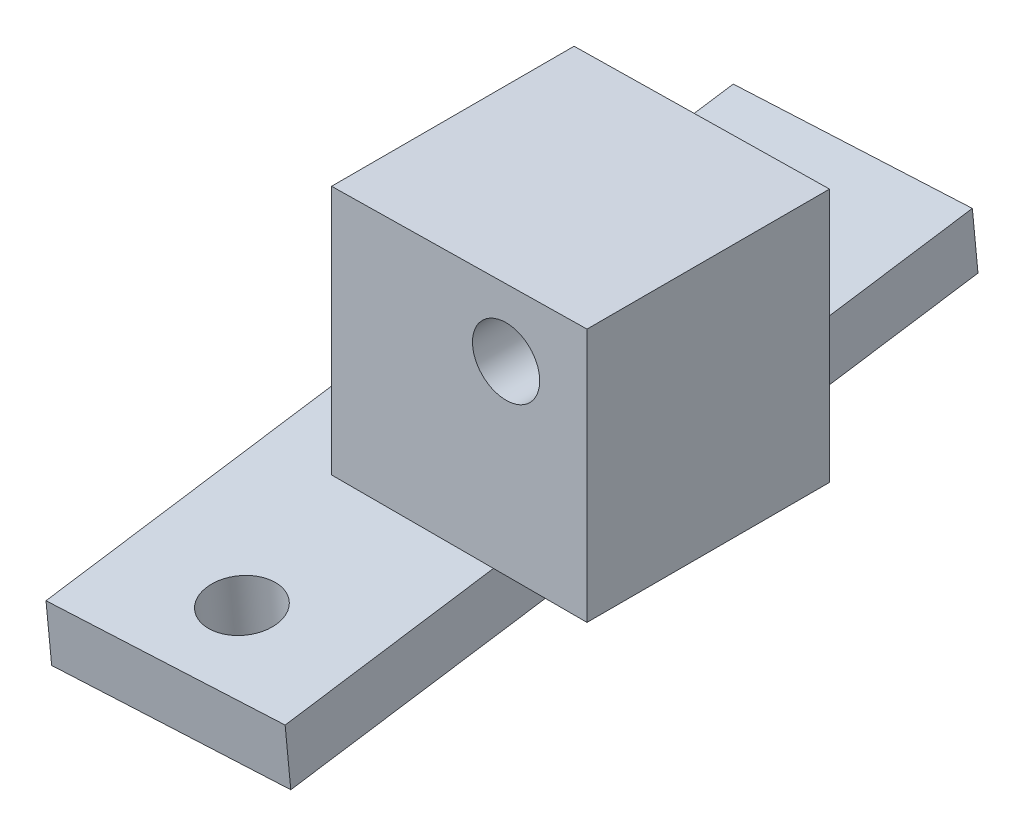
SolidWorks part; units mm, degrees
ref_plane "Front Plane" through (0, 0, 0) normal (0, 0, 1) x (1, 0, 0)
ref_plane "Top Plane" through (0, 0, 0) normal (0, 1, 0) x (1, 0, 0)
ref_plane "Right Plane" through (0, 0, 0) normal (1, 0, 0) x (0, 0, -1)
sketch "Sketch1" plane through (0, 0, 0) normal (0, 0, 1) x (1, 0, 0)
  line L4 (-277.3561, 264.2791) -> (-301.4861, 263.9)
  line L5 (-301.4861, 263.9) -> (-301.4861, 241.3438)
  line L6 (-301.4861, 241.3438) -> (-277.3561, 241.7228)
  line L7 (-277.3561, 241.7228) -> (-277.3561, 264.2791)
  circle A0 centre (-285, 257.8082) radius 3.175
  dimension "D6" = 6.35
  dimension "D1" = 3.81
  dimension "D2" = 3.81
  dimension "D3" = 24.13
  dimension "D4" = 22.5535
  dimension "D5" = 6.35
extrude "Boss-Extrude3" add sketch "Sketch1" along normal up to surface (22.9108 mm away) contours L7 L4 L5 L6 | A0
ref_plane "Plane1" through (0, 240.2331, 23.0373) normal (0, 0.9954, 0.0955) x (1, 0, 0)
sketch "Sketch2" plane through (0, 240.2331, 23.0373) normal (0, 0.9954, 0.0955) x (1, 0, 0)
  line L0 (-310.0689, 46.8658) -> (-306.7997, -21.6362)
  line L1 (-306.7997, -21.6362) -> (-285.2343, -20.607)
  line L2 (-285.2343, -20.607) -> (-288.5034, 47.895)
  line L3 (-288.5034, 47.895) -> (-310.0689, 46.8658)
  line L4 (-301.4861, 23.0381) -> (-277.3561, 23.0743) construction
  circle A0 centre (-298.9229, 39.7691) radius 3.175
  circle A1 centre (-296.3802, -13.5103) radius 3.175
  dimension "D6" = 10.795
  dimension "D9" = 6.35
  dimension "D10" = 6.35
  dimension "D1" = 87.354
  dimension "D2" = 21.59
  dimension "D3" = 6.35
  dimension "D4" = 21.59
  dimension "D5" = 68.58
  dimension "D7" = 10.795
  dimension "D8" = 7.62
  dimension "D11" = 7.62
extrude "Boss-Extrude4" add sketch "Sketch2" against normal blind 5.588
sketch "Sketch5" plane through (0, 0, 22.9108) normal (0, 0, 1) x (1, 0, 0)
  line L0 (-301.4861, 241.3438) -> (-301.4861, 240.2807)
  line L1 (-301.4861, 240.2807) -> (-277.3561, 240.2807)
  line L2 (-277.3561, 240.2807) -> (-277.3561, 241.7228)
  line L3 (-277.3561, 241.7228) -> (-301.4861, 241.3438)
extrude "Boss-Extrude5" add sketch "Sketch5" against normal up to surface (22.9108 mm away) up to face at (-288.7208, 249.3921, 0)
